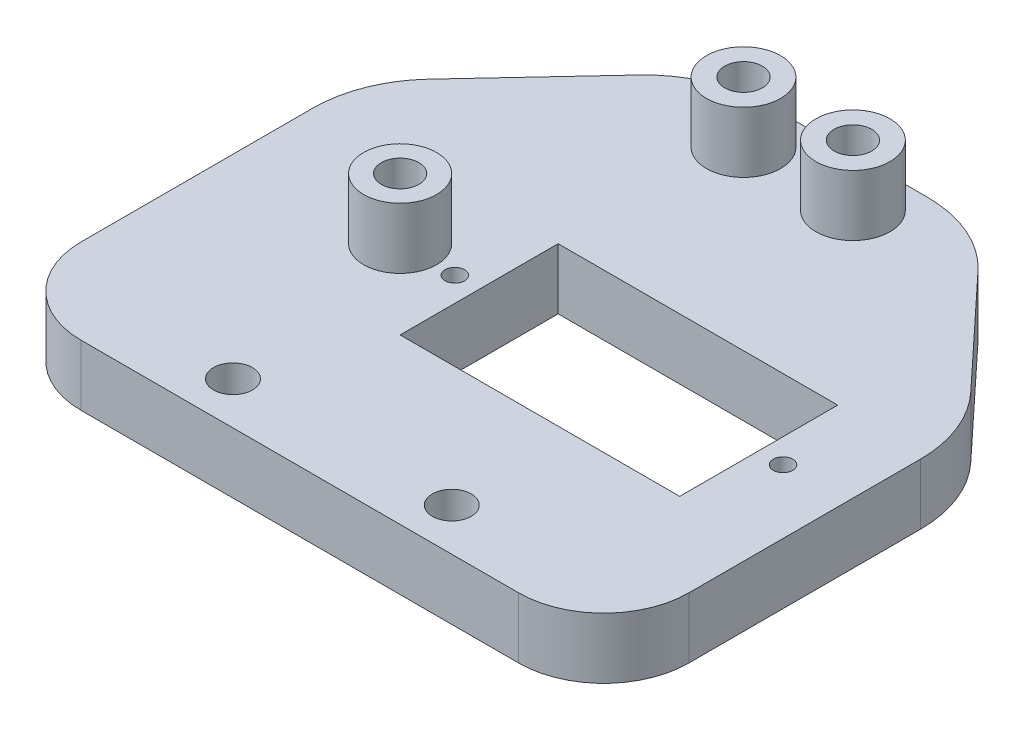
SolidWorks part; units mm, degrees
ref_plane "前视基准面" through (0, 0, 0) normal (0, 0, 1) x (1, 0, 0)
ref_plane "上视基准面" through (0, 0, 0) normal (0, 1, 0) x (1, 0, 0)
ref_plane "右视基准面" through (0, 0, 0) normal (1, 0, 0) x (0, 0, -1)
sketch "草图1" plane through (0, 0, 0) normal (0, 1, 0) x (1, 0, 0)
  line L0 (-11, 30) -> (-25, 15)
  line L2 (-25, 15) -> (-25, -15)
  line L3 (-25, -15) -> (25, -15)
  line L4 (25, 15) -> (25, -15)
  line L5 (-25, 15) -> (25, -15) construction
  line L6 (-25, -15) -> (25, 15) construction
  line L7 (-11, 30) -> (11, 30)
  line L11 (0, -55) -> (0, 55) construction
  line L13 (11, 30) -> (25, 15)
  circle A0 centre (-11.75, 5) radius 1.55
  circle A1 centre (11.75, 5) radius 1.55
  point P0 (0, 0)
  point P6 (0, 22.5)
  dimension "D3" = 3.1
  dimension "D1" = 50
  dimension "D2" = 22
  dimension "D4" = 45
  dimension "D5" = 20
  dimension "D6" = 11.75
extrude "凸台-拉伸1" add sketch "草图1" along normal blind 5
sketch "草图2" plane through (0, 5, 0) normal (0, 1, 0) x (1, 0, 0)
  line L0 (11, 30) -> (-11, 30) construction
  line L1 (0, -55) -> (0, 55) construction
  circle A0 centre (-4.5, 26) radius 1.55
  circle A1 centre (4.5, 26) radius 1.55
  dimension "D1" = 3.1
  dimension "D2" = 4
  dimension "D3" = 4.5
extrude "切除-拉伸1" cut sketch "草图2" against normal blind 5
fillet "圆角1" radius 10 4 edges at (25, 2.5, -15) (11, 2.5, -30) (-11, 2.5, -30) (-25, 2.5, -15)
sketch "草图4" plane through (0, 0, 0) normal (0, -1, 0) x (1, 0, 0)
  line L0 (6.25, 1.5) -> (6.25, -3.3347) construction
  line L1 (-5.25, 1.5) -> (17.75, 1.5)
  line L2 (-5.25, 1.5) -> (-5.25, -11.5)
  line L3 (-5.25, -11.5) -> (17.75, -11.5)
  line L4 (17.75, 1.5) -> (17.75, -11.5)
  circle A0 centre (11.75, -5) radius 1.55 construction
  circle A1 centre (11.75, -5) radius 1.55
  circle A2 centre (19.75, -5) radius 0.8
  circle A3 centre (-7.25, -5) radius 0.8
  point P7 (17.75, -5)
  dimension "D4" = 1.6
  dimension "D1" = 6
  dimension "D2" = 17
  dimension "D3" = 13
  dimension "D5" = 27
extrude "切除-拉伸2" cut sketch "草图4" against normal blind 5
sketch "草图5" plane through (0, 5, 0) normal (0, 1, 0) x (1, 0, 0)
  circle A0 centre (-4.5, 26) radius 1.55 construction
  circle A1 centre (-4.5, 26) radius 1.55
  circle A3 centre (4.5, 26) radius 1.55 construction
  circle A5 centre (4.5, 26) radius 1.55
  circle A6 centre (-4.5, 26) radius 3.05
  circle A7 centre (4.5, 26) radius 3.05
  circle A11 centre (-11.75, 5) radius 3
  dimension "D2" = 6
  dimension "D1" = 1.5
extrude "凸台-拉伸2" add sketch "草图5" along normal blind 5
sketch "草图6" plane through (0, 5, 0) normal (0, 1, 0) x (1, 0, 0)
  line L0 (25, -15) -> (25, 11.0584) construction
  line L1 (-25, -15) -> (25, -15)
  line L2 (-25, -15) -> (-25, -10)
  line L4 (25, -15) -> (25, -10)
  line L5 (0, -10) -> (0, -15) construction
  circle A0 centre (-9, -11.5) radius 1.6
  circle A1 centre (9, -11.5) radius 1.6
  dimension "D2" = 9
  dimension "D3" = 3.5
sketch "草图8" plane through (0, 0, 0) normal (0, -1, 0) x (1, 0, 0)
  circle A0 centre (-11.75, -5) radius 1.55 construction
  circle A1 centre (-11.75, -5) radius 1.55
extrude "切除-拉伸4" cut sketch "草图8" against normal blind 11
extrude "切除-拉伸6" cut sketch "草图6" against normal blind 10 contours A0 | A1
chamfer "倒角1" distance 0.3 angle 45 2 edges at (9, 0, 13.1) (-9, 0, 13.1)
fillet "圆角2" radius 7 2 edges at (-25, 2.5, 15) (25, 2.5, 15)
